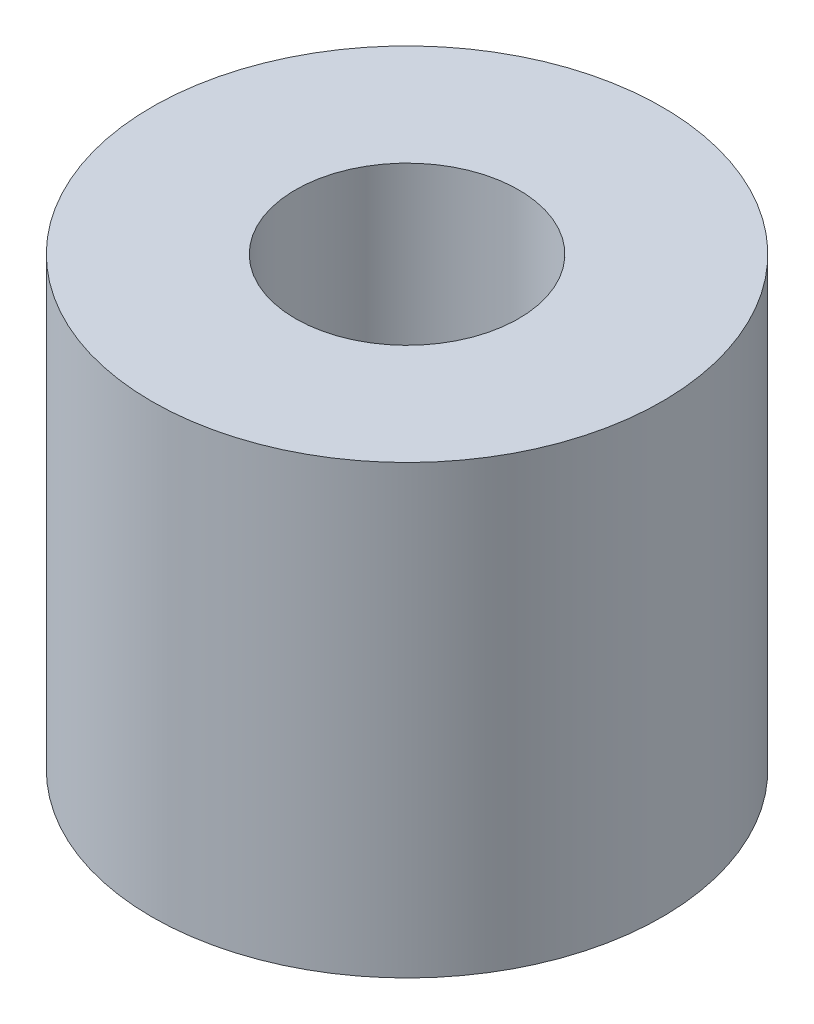
SolidWorks part; units mm, degrees
ref_plane "前视基准面" through (0, 0, 0) normal (0, 0, 1) x (1, 0, 0)
ref_plane "上视基准面" through (0, 0, 0) normal (0, 1, 0) x (1, 0, 0)
ref_plane "右视基准面" through (0, 0, 0) normal (1, 0, 0) x (0, 0, -1)
sketch "草图1" plane through (0, 0, 0) normal (0, 1, 0) x (1, 0, 0)
  circle A0 centre (0, 0) radius 1.75
  circle A1 centre (0, 0) radius 4
  dimension "D1" = 3.5
  dimension "D2" = 8
extrude "凸台-拉伸1" add sketch "草图1" along normal blind 7
